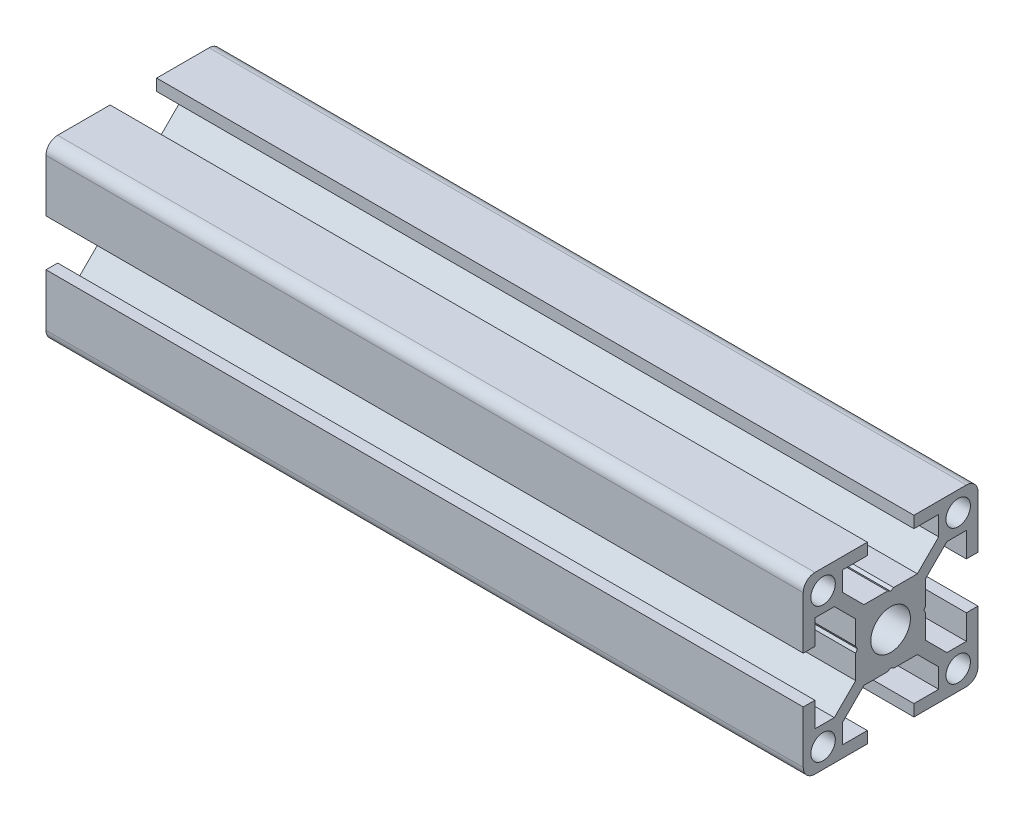
SolidWorks part; units mm, degrees
ref_plane "Front Plane" through (0, 0, 0) normal (0, 0, 1) x (1, 0, 0)
ref_plane "Top Plane" through (0, 0, 0) normal (0, 1, 0) x (1, 0, 0)
ref_plane "Right Plane" through (0, 0, 0) normal (1, 0, 0) x (0, 0, -1)
sketch "Sketch1" plane through (0, 0, 0) normal (0, 0, 1) x (1, 0, 0)
  line L0 (0, 0) -> (130, 0)
  dimension "D1" = 130
other "Ðnh hình 30X30X2(1)"
ref_plane "Plane2" through (0, 0, 0) normal (1, 0, 0) x (0, 1, 0)
sketch "Sketch12" plane through (0, 0, 0) normal (1, 0, 0) x (0, 1, 0)
  line L0 (13, -4) -> (13, -8.25)
  line L1 (13, -8.25) -> (9.6642, -8.25)
  line L2 (9.6642, -8.25) -> (6, -4.5858)
  line L3 (6, -4.5858) -> (6, -0.5196)
  line L4 (6, -0.5196) -> (5.7, 0)
  line L5 (5.7, 0) -> (6, 0.5196)
  line L6 (6, 0.5196) -> (6, 4.5858)
  line L7 (6, 4.5858) -> (9.6642, 8.25)
  line L8 (9.6642, 8.25) -> (13, 8.25)
  line L9 (13, 8.25) -> (13, 4)
  line L10 (13, 4) -> (15, 4)
  line L11 (15, 4) -> (15, 13)
  line L12 (13, 15) -> (4, 15)
  line L13 (4, 15) -> (4, 13)
  line L14 (4, 13) -> (8.25, 13)
  line L15 (8.25, 13) -> (8.25, 9.6642)
  line L16 (8.25, 9.6642) -> (4.5858, 6)
  line L17 (4.5858, 6) -> (0.5196, 6)
  line L18 (0.5196, 6) -> (0, 5.7)
  line L19 (0, 5.7) -> (-0.5196, 6)
  line L20 (-0.5196, 6) -> (-4.5858, 6)
  line L21 (-4.5858, 6) -> (-8.25, 9.6642)
  line L22 (-8.25, 9.6642) -> (-8.25, 13)
  line L23 (-8.25, 13) -> (-4, 13)
  line L24 (-4, 13) -> (-4, 15)
  line L25 (-4, 15) -> (-13, 15)
  line L26 (-15, 13) -> (-15, 4)
  line L27 (-15, 4) -> (-13, 4)
  line L28 (-13, 4) -> (-13, 8.25)
  line L29 (-13, 8.25) -> (-9.6642, 8.25)
  line L30 (-9.6642, 8.25) -> (-6, 4.5858)
  line L31 (-6, 4.5858) -> (-6, 0.5196)
  line L32 (-6, 0.5196) -> (-5.7, 0)
  line L33 (-5.7, 0) -> (-6, -0.5196)
  line L34 (-6, -0.5196) -> (-6, -4.5858)
  line L35 (-6, -4.5858) -> (-9.6642, -8.25)
  line L36 (-9.6642, -8.25) -> (-13, -8.25)
  line L37 (-13, -8.25) -> (-13, -4)
  line L38 (-13, -4) -> (-15, -4)
  line L39 (-15, -4) -> (-15, -13)
  line L40 (-13, -15) -> (-4, -15)
  line L41 (-4, -15) -> (-4, -13)
  line L42 (-4, -13) -> (-8.25, -13)
  line L43 (-8.25, -13) -> (-8.25, -9.6642)
  line L44 (-8.25, -9.6642) -> (-4.5858, -6)
  line L45 (-4.5858, -6) -> (-0.5196, -6)
  line L46 (-0.5196, -6) -> (0, -5.7)
  line L47 (0, -5.7) -> (0.5196, -6)
  line L48 (0.5196, -6) -> (4.5858, -6)
  line L49 (4.5858, -6) -> (8.25, -9.6642)
  line L50 (8.25, -9.6642) -> (8.25, -13)
  line L51 (8.25, -13) -> (4, -13)
  line L52 (4, -13) -> (4, -15)
  line L53 (4, -15) -> (13, -15)
  line L54 (15, -13) -> (15, -4)
  line L55 (15, -4) -> (13, -4)
  arc A0 (15, 13) -> (13, 15) centre (13, 13) ccw
  arc A1 (-13, 15) -> (-15, 13) centre (-13, 13) ccw
  arc A2 (-15, -13) -> (-13, -15) centre (-13, -13) ccw
  arc A3 (13, -15) -> (15, -13) centre (13, -13) ccw
  circle A4 centre (0, 0) radius 3.4
  circle A5 centre (11.6, -11.6) radius 2.1
  circle A6 centre (11.6, 11.6) radius 2.1
  circle A7 centre (-11.6, 11.6) radius 2.1
  circle A8 centre (-11.6, -11.6) radius 2.1
  point P74 (0, 0)
